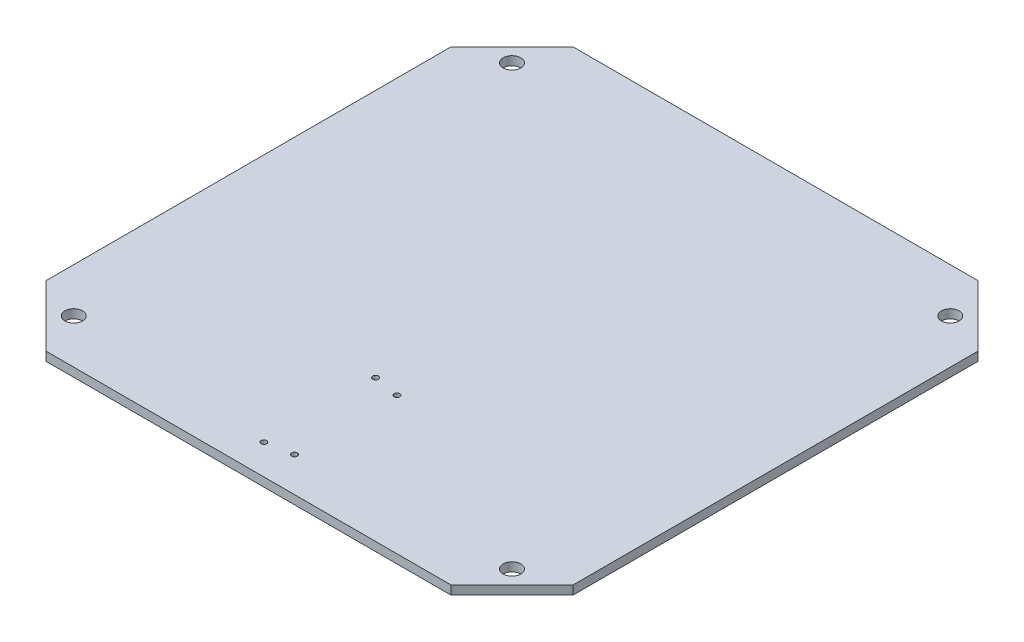
SolidWorks part; units mm, degrees
ref_plane "Front Plane" through (0, 0, 0) normal (0, 0, 1) x (1, 0, 0)
ref_plane "Top Plane" through (0, 0, 0) normal (0, 1, 0) x (1, 0, 0)
ref_plane "Right Plane" through (0, 0, 0) normal (1, 0, 0) x (0, 0, -1)
sketch "Sketch1" plane through (0, 0, 0) normal (0, 1, 0) x (1, 0, 0)
  line L0 (-47.5, 36.5) -> (-36.5, 47.5)
  line L1 (-36.5, 47.5) -> (36.5, 47.5)
  line L2 (-47.5, 36.5) -> (-47.5, -36.5)
  line L3 (-36.5, -47.5) -> (36.5, -47.5)
  line L4 (47.5, 36.5) -> (47.5, -36.5)
  line L5 (-42, 42) -> (42, -42) construction
  line L6 (-42, -42) -> (42, 42) construction
  line L7 (36.5, 47.5) -> (47.5, 36.5)
  line L8 (47.5, -36.5) -> (36.5, -47.5)
  line L9 (-36.5, -47.5) -> (-47.5, -36.5)
  point P0 (0, 0)
  dimension "D1" = 95
  dimension "D2" = 95
  dimension "D3" = 11
  dimension "D4" = 11
  dimension "D5" = 11
  dimension "D6" = 11
  dimension "D7" = 11
  dimension "D8" = 11
  dimension "D9" = 11
  dimension "D10" = 11
extrude "Boss-Extrude1" add sketch "Sketch1" along normal blind 1.59 contours L2 L9 L3 L8 L4 L7 L1 L0
sketch "Sketch2" plane through (0, 1.59, 0) normal (0, 1, 0) x (1, 0, 0)
  line L0 (-36.5, -47.5) -> (36.5, -47.5) construction
  line L1 (-47.5, 36.5) -> (-47.5, -36.5) construction
  line L2 (-36.5, 47.5) -> (36.5, 47.5) construction
  line L3 (47.5, 36.5) -> (47.5, -36.5) construction
  circle A0 centre (-39.5, 39.5) radius 1.59
  circle A1 centre (-39.5, -39.5) radius 1.59
  circle A2 centre (39.5, -39.5) radius 1.59
  circle A3 centre (39.5, 39.5) radius 1.59
  circle A4 centre (-2.67, -21.93) radius 0.51
  circle A5 centre (2.03, -22.75) radius 0.51
  circle A6 centre (-2.67, -42.07) radius 0.51
  circle A7 centre (2.03, -41.24) radius 0.51
  dimension "D1" = 3.18
  dimension "D2" = 8
  dimension "D10" = 1.02
  dimension "D3" = 8
  dimension "D4" = 8
  dimension "D5" = 8
  dimension "D6" = 8
  dimension "D7" = 8
  dimension "D8" = 8
  dimension "D9" = 8
  dimension "D11" = 44.83
  dimension "D12" = 49.53
  dimension "D13" = 44.83
  dimension "D14" = 49.53
  dimension "D15" = 5.43
  dimension "D16" = 6.26
  dimension "D17" = 25.57
  dimension "D18" = 24.75
extrude "Cut-Extrude2" cut sketch "Sketch2" against normal through all
